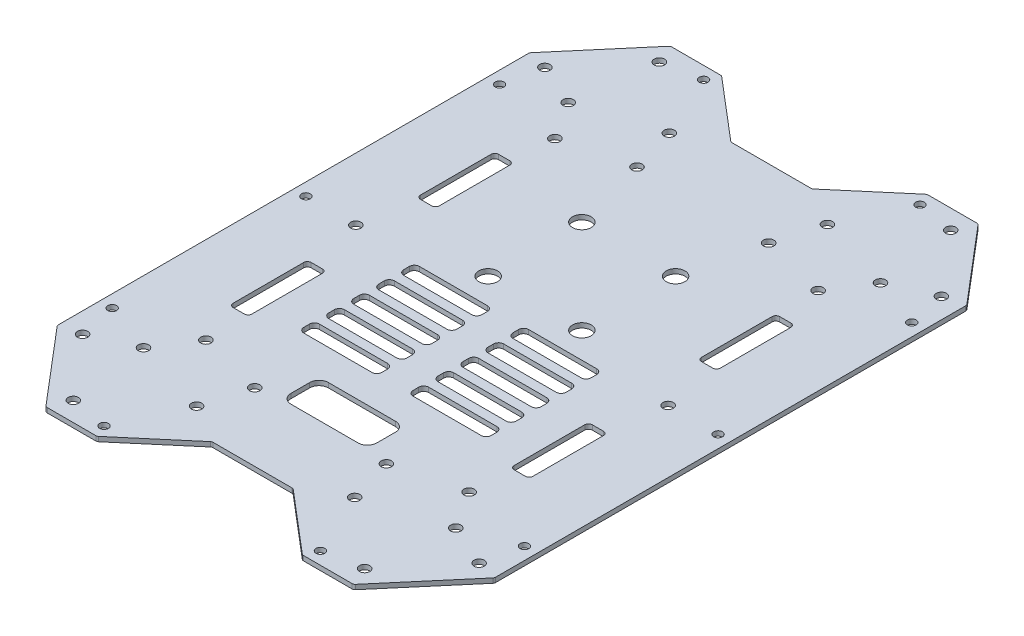
SolidWorks part; units mm, degrees
material "Custom Plastic"
ref_plane "Front Plane" through (0, 0, 0) normal (0, 0, 1) x (1, 0, 0)
ref_plane "Top Plane" through (0, 0, 0) normal (0, 1, 0) x (1, 0, 0)
ref_plane "Right Plane" through (0, 0, 0) normal (1, 0, 0) x (0, 0, -1)
sketch "Sketch1" plane through (0, 0, 0) normal (0, 1, 0) x (1, 0, 0)
  line L0 (49.2748, 100) -> (-49.2748, 100) construction
  line L1 (-49.2748, 100) -> (-70, 75.6183) construction
  line L2 (-70, -75.6183) -> (-70, 75.6183) construction
  line L3 (-49.2748, -100) -> (-70, -75.6183) construction
  line L4 (49.2748, -100) -> (-49.2748, -100) construction
  line L5 (49.2748, -100) -> (70, -75.6183) construction
  line L6 (70, -75.6183) -> (70, 75.6183) construction
  line L7 (49.2748, 100) -> (70, 75.6183) construction
  line L8 (49.2748, 100) -> (-49.2748, 100)
  line L9 (-49.2748, 100) -> (-70, 75.6183)
  line L10 (-70, -75.6183) -> (-70, 75.6183)
  line L11 (-49.2748, -100) -> (-70, -75.6183)
  line L12 (49.2748, -100) -> (-49.2748, -100)
  line L13 (49.2748, -100) -> (70, -75.6183)
  line L14 (70, -75.6183) -> (70, 75.6183)
  line L15 (49.2748, 100) -> (70, 75.6183)
  line L16 (247.4874, -247.4874) -> (29.1603, -61.9027) construction
  line L18 (-29.1603, -61.9027) -> (-247.4874, -247.4874) construction
  line L20 (-247.4874, 247.4874) -> (-29.1603, 61.9027) construction
  line L21 (247.4874, 247.4874) -> (29.1603, 61.9027) construction
  line L22 (247.4874, -247.4874) -> (29.1603, -61.9027) construction
  line L24 (-29.1603, -61.9027) -> (-247.4874, -247.4874) construction
  line L26 (-247.4874, 247.4874) -> (-29.1603, 61.9027) construction
  line L27 (247.4874, 247.4874) -> (29.1603, 61.9027) construction
extrude "Boss-Extrude1" add sketch "Sketch1" along normal blind 1.5
sketch "Sketch2" plane through (0, 0, 0) normal (0, 1, 0) x (1, 0, 0)
  line L0 (0, 100) -> (0, -100) construction
  line L1 (49.2748, 100) -> (-49.2748, 100) construction
  line L2 (49.2748, -100) -> (-49.2748, -100) construction
  line L8 (42, 18.7) -> (42, 41.3)
  line L47 (43.2, 17.5) -> (46.8, 17.5)
  line L48 (48, 18.7) -> (48, 41.3)
  line L49 (43.2, 42.5) -> (46.8, 42.5)
  line L50 (-48, 18.7) -> (-48, 41.3)
  line L51 (-46.8, 17.5) -> (-43.2, 17.5)
  line L52 (-42, 18.7) -> (-42, 41.3)
  line L53 (-46.8, 42.5) -> (-43.2, 42.5)
  line L54 (-70, 0) -> (70, 0) construction
  line L55 (-70, 75.6183) -> (-70, -75.6183) construction
  line L56 (70, -75.6183) -> (70, 75.6183) construction
  line L59 (-46.8, -42.5) -> (-43.2, -42.5)
  line L60 (-42, -18.7) -> (-42, -41.3)
  line L61 (-46.8, -17.5) -> (-43.2, -17.5)
  line L62 (-48, -18.7) -> (-48, -41.3)
  line L63 (43.2, -42.5) -> (46.8, -42.5)
  line L64 (48, -18.7) -> (48, -41.3)
  line L65 (43.2, -17.5) -> (46.8, -17.5)
  line L70 (42, -18.7) -> (42, -41.3)
  arc A40 (42, 41.3) -> (43.2, 42.5) centre (43.2, 41.3) cw
  arc A41 (43.2, 17.5) -> (42, 18.7) centre (43.2, 18.7) cw
  arc A42 (48, 18.7) -> (46.8, 17.5) centre (46.8, 18.7) cw
  arc A43 (46.8, 42.5) -> (48, 41.3) centre (46.8, 41.3) cw
  arc A44 (-48, 41.3) -> (-46.8, 42.5) centre (-46.8, 41.3) cw
  arc A45 (-46.8, 17.5) -> (-48, 18.7) centre (-46.8, 18.7) cw
  arc A46 (-42, 18.7) -> (-43.2, 17.5) centre (-43.2, 18.7) cw
  arc A47 (-43.2, 42.5) -> (-42, 41.3) centre (-43.2, 41.3) cw
  arc A48 (-43.2, -42.5) -> (-42, -41.3) centre (-43.2, -41.3) ccw
  arc A49 (-42, -18.7) -> (-43.2, -17.5) centre (-43.2, -18.7) ccw
  arc A50 (-46.8, -17.5) -> (-48, -18.7) centre (-46.8, -18.7) ccw
  arc A51 (-48, -41.3) -> (-46.8, -42.5) centre (-46.8, -41.3) ccw
  arc A52 (46.8, -42.5) -> (48, -41.3) centre (46.8, -41.3) ccw
  arc A53 (48, -18.7) -> (46.8, -17.5) centre (46.8, -18.7) ccw
  arc A54 (43.2, -17.5) -> (42, -18.7) centre (43.2, -18.7) ccw
  arc A55 (42, -41.3) -> (43.2, -42.5) centre (43.2, -41.3) ccw
extrude "Cut-Extrude1" cut sketch "Sketch2" along normal through all
sketch "Sketch3" plane through (0, 0, 0) normal (0, 1, 0) x (1, 0, 0)
  circle A0 centre (-25.3123, -75.6937) radius 1.65
  circle A1 centre (-46.6462, -93.8282) radius 1.65
  circle A2 centre (-63.4854, -74.0181) radius 1.65
  circle A3 centre (-42.1515, -55.8836) radius 1.65
  circle A4 centre (25.3123, -75.6937) radius 1.65
  circle A5 centre (46.6462, -93.8282) radius 1.65
  circle A6 centre (63.4854, -74.0181) radius 1.65
  circle A7 centre (42.1515, -55.8836) radius 1.65
  circle A8 centre (42.1515, 55.8836) radius 1.65
  circle A9 centre (63.4854, 74.0181) radius 1.65
  circle A10 centre (46.6462, 93.8282) radius 1.65
  circle A11 centre (25.3123, 75.6937) radius 1.65
  circle A12 centre (-25.3123, 75.6937) radius 1.65
  circle A13 centre (-42.1515, 55.8836) radius 1.65
  circle A14 centre (-63.4854, 74.0181) radius 1.65
  circle A15 centre (-46.6462, 93.8282) radius 1.65
  dimension "D1" = 3.3
extrude "Cut-Extrude2" cut sketch "Sketch3" along normal through all
sketch "Sketch5" plane through (0, 0, 0) normal (0, 1, 0) x (1, 0, 0)
  line L0 (50, -90) -> (50, 90) construction
  line L1 (-20, -20) -> (20, -20) construction
  line L2 (-20, -20) -> (-20, 20) construction
  line L3 (-20, 20) -> (20, 20) construction
  line L4 (20, -20) -> (20, 20) construction
  line L5 (-20, -20) -> (20, 20) construction
  line L6 (-20, 20) -> (20, -20) construction
  line L7 (48.7071, -90) -> (51.2929, -90) construction
  line L8 (48.7071, 90) -> (51.2929, 90) construction
  circle A14 centre (21.059, -61.2942) radius 1.65
  circle A15 centre (-21.105, -61.2942) radius 1.65
  circle A16 centre (21.059, 61.1338) radius 1.65
  circle A17 centre (-21.105, 61.1338) radius 1.65
  circle A18 centre (15.358, 37.0178) radius 3
  circle A19 centre (-14.642, 37.0178) radius 3
  circle A20 centre (-14.642, 7.0178) radius 3
  circle A21 centre (15.358, 7.0178) radius 3
  point P0 (0, 0)
  dimension "D1" = 3.3
  dimension "D4" = 6
  dimension "D2" = 40
  dimension "D3" = 40
extrude "Cut-Extrude5" cut sketch "Sketch5" along normal through all
sketch "Sketch6" plane through (0, 0, 0) normal (0, 1, 0) x (1, 0, 0)
  line L0 (-50, -90) -> (-50, 90) construction
  line L1 (-51.2929, -90) -> (-48.7071, -90) construction
  line L2 (-51.2929, 90) -> (-48.7071, 90) construction
  line L3 (0, -100) -> (0, 100) construction
  line L4 (-49.2748, -100) -> (49.2748, -100) construction
  line L5 (49.2748, 100) -> (-49.2748, 100) construction
  line L6 (50, -90) -> (50, 90) construction
  circle A0 centre (-50, 0) radius 1.65
  circle A1 centre (-50, -68) radius 1.65
  circle A2 centre (-50, 68) radius 1.65
  circle A3 centre (50, 68) radius 1.65
  circle A4 centre (50, -68) radius 1.65
  circle A5 centre (50, 0) radius 1.65
  dimension "D1" = 3.3
  dimension "D2" = 68
  dimension "D3" = 68
extrude "Cut-Extrude6" cut sketch "Sketch6" along normal through all
sketch "Sketch7" plane through (0, 0, 0) normal (0, 1, 0) x (1, 0, 0)
  line L0 (0, -100) -> (0, 100) construction
  line L1 (-49.2748, -100) -> (49.2748, -100) construction
  line L2 (49.2748, 100) -> (-49.2748, 100) construction
  line L3 (-70, 75.6183) -> (-70, -75.6183) construction
  line L4 (-70, 0) -> (-66, 0) construction
  line L5 (70, 0) -> (66, 0) construction
  circle A0 centre (-34.6462, -96) radius 1.4
  circle A1 centre (-46.6462, -93.8282) radius 1.65 construction
  circle A2 centre (-66, -62.0181) radius 1.4
  circle A3 centre (-63.4854, -74.0181) radius 1.65 construction
  circle A4 centre (-66, 0) radius 1.4
  circle A5 centre (-66, 62.0181) radius 1.4
  circle A6 centre (-63.4854, 74.0181) radius 1.65 construction
  circle A7 centre (-34.6462, 96) radius 1.4
  circle A8 centre (-46.6462, 93.8282) radius 1.65 construction
  circle A9 centre (0, 96) radius 1.4
  circle A10 centre (0, -96) radius 1.4
  circle A11 centre (34.6462, 96) radius 1.4
  circle A12 centre (66, 62.0181) radius 1.4
  circle A13 centre (66, 0) radius 1.4
  circle A14 centre (66, -62.0181) radius 1.4
  circle A15 centre (34.6462, -96) radius 1.4
  dimension "D2" = 2.8
  dimension "D1" = 4
  dimension "D3" = 12
  dimension "D4" = 4
  dimension "D5" = 12
  dimension "D6" = 4
  dimension "D7" = 4
  dimension "D8" = 12
  dimension "D9" = 4
  dimension "D10" = 12
  dimension "D11" = 4
  dimension "D12" = 4
extrude "Cut-Extrude7" cut sketch "Sketch7" along normal through all
sketch "Sketch9" [suppressed] plane through (0, 0, 0) normal (0, 1, 0) x (1, 0, 0)
  line L0 (0, -100) -> (0, 100) construction
  line L1 (-49.2748, -100) -> (49.2748, -100) construction
  line L2 (49.2748, 100) -> (-49.2748, 100) construction
  line L4 (-14.5, 42.1059) -> (14.5, 42.1059)
  line L5 (-20, 36.6059) -> (-20, 7.6059)
  line L6 (-14.5, 2.1059) -> (14.5, 2.1059)
  line L7 (20, 36.6059) -> (20, 7.6059)
  line L8 (-20, 42.1059) -> (20, 2.1059) construction
  line L9 (-20, 2.1059) -> (20, 42.1059) construction
  arc A0 (-14.5, 42.1059) -> (-20, 36.6059) centre (-14.5, 36.6059) ccw
  arc A1 (14.5, 42.1059) -> (20, 36.6059) centre (14.5, 36.6059) cw
  arc A2 (14.5, 2.1059) -> (20, 7.6059) centre (14.5, 7.6059) ccw
  arc A3 (-20, 7.6059) -> (-14.5, 2.1059) centre (-14.5, 7.6059) ccw
  point P6 (0, 22.1059)
  dimension "D2" = 5.5
  dimension "D1" = 40
extrude "Cut-Extrude9" [suppressed] cut sketch "Sketch9" along normal through all
sketch "Sketch10" plane through (0, 0, 0) normal (0, 1, 0) x (1, 0, 0)
  line L0 (0, 100) -> (0, -100) construction
  line L1 (49.2748, 100) -> (-49.2748, 100) construction
  line L2 (-49.2748, -100) -> (49.2748, -100) construction
  line L3 (-5, -10.8698) -> (-5, -12.6698)
  line L4 (-10.75, -60.0405) -> (10.75, -60.0405)
  line L5 (-13.75, -57.0405) -> (-13.75, -51.0405)
  line L6 (-10.75, -48.0405) -> (10.75, -48.0405)
  line L7 (13.75, -57.0405) -> (13.75, -51.0405)
  line L8 (-13.75, -60.0405) -> (13.75, -48.0405) construction
  line L9 (-13.75, -48.0405) -> (13.75, -60.0405) construction
  line L10 (-6.6, -1.2698) -> (-28.4, -1.2698)
  line L11 (-5, -2.8698) -> (-5, -4.6698)
  line L12 (-6.6, -6.2698) -> (-28.4, -6.2698)
  line L13 (-30, -2.8698) -> (-30, -4.6698)
  line L14 (-5, -1.2698) -> (-30, -6.2698) construction
  line L15 (-5, -6.2698) -> (-30, -1.2698) construction
  line L16 (-6.6, -9.2698) -> (-28.4, -9.2698)
  line L17 (-30, -10.8698) -> (-30, -12.6698)
  line L18 (-6.6, -14.2698) -> (-28.4, -14.2698)
  line L19 (-5, -18.8698) -> (-5, -20.6698)
  line L20 (-6.6, -17.2698) -> (-28.4, -17.2698)
  line L21 (-30, -18.8698) -> (-30, -20.6698)
  line L22 (-6.6, -22.2698) -> (-28.4, -22.2698)
  line L23 (-5, -26.8698) -> (-5, -28.6698)
  line L24 (-6.6, -25.2698) -> (-28.4, -25.2698)
  line L25 (-30, -26.8698) -> (-30, -28.6698)
  line L26 (-6.6, -30.2698) -> (-28.4, -30.2698)
  line L27 (-5, -34.8698) -> (-5, -36.6698)
  line L28 (-6.6, -33.2698) -> (-28.4, -33.2698)
  line L29 (-30, -34.8698) -> (-30, -36.6698)
  line L30 (-6.6, -38.2698) -> (-28.4, -38.2698)
  line L31 (5, -6.2698) -> (30, -1.2698) construction
  line L32 (5, -1.2698) -> (30, -6.2698) construction
  line L33 (6.6, -38.2698) -> (28.4, -38.2698)
  line L34 (30, -34.8698) -> (30, -36.6698)
  line L35 (6.6, -33.2698) -> (28.4, -33.2698)
  line L36 (5, -34.8698) -> (5, -36.6698)
  line L37 (6.6, -30.2698) -> (28.4, -30.2698)
  line L38 (30, -26.8698) -> (30, -28.6698)
  line L39 (6.6, -25.2698) -> (28.4, -25.2698)
  line L40 (5, -26.8698) -> (5, -28.6698)
  line L41 (6.6, -22.2698) -> (28.4, -22.2698)
  line L42 (30, -18.8698) -> (30, -20.6698)
  line L43 (6.6, -17.2698) -> (28.4, -17.2698)
  line L44 (5, -18.8698) -> (5, -20.6698)
  line L45 (6.6, -14.2698) -> (28.4, -14.2698)
  line L46 (30, -10.8698) -> (30, -12.6698)
  line L47 (6.6, -9.2698) -> (28.4, -9.2698)
  line L48 (30, -2.8698) -> (30, -4.6698)
  line L49 (6.6, -6.2698) -> (28.4, -6.2698)
  line L50 (5, -2.8698) -> (5, -4.6698)
  line L51 (6.6, -1.2698) -> (28.4, -1.2698)
  line L52 (5, -10.8698) -> (5, -12.6698)
  arc A0 (-13.75, -51.0405) -> (-10.75, -48.0405) centre (-10.75, -51.0405) cw
  arc A1 (-10.75, -60.0405) -> (-13.75, -57.0405) centre (-10.75, -57.0405) cw
  arc A2 (10.75, -60.0405) -> (13.75, -57.0405) centre (10.75, -57.0405) ccw
  arc A3 (10.75, -48.0405) -> (13.75, -51.0405) centre (10.75, -51.0405) cw
  arc A4 (-28.4, -6.2698) -> (-30, -4.6698) centre (-28.4, -4.6698) cw
  arc A5 (-5, -4.6698) -> (-6.6, -6.2698) centre (-6.6, -4.6698) cw
  arc A6 (-6.6, -1.2698) -> (-5, -2.8698) centre (-6.6, -2.8698) cw
  arc A7 (-28.4, -1.2698) -> (-30, -2.8698) centre (-28.4, -2.8698) ccw
  arc A8 (-6.6, -9.2698) -> (-5, -10.8698) centre (-6.6, -10.8698) cw
  arc A9 (-5, -12.6698) -> (-6.6, -14.2698) centre (-6.6, -12.6698) cw
  arc A10 (-28.4, -9.2698) -> (-30, -10.8698) centre (-28.4, -10.8698) ccw
  arc A11 (-28.4, -14.2698) -> (-30, -12.6698) centre (-28.4, -12.6698) cw
  arc A12 (-6.6, -17.2698) -> (-5, -18.8698) centre (-6.6, -18.8698) cw
  arc A13 (-5, -20.6698) -> (-6.6, -22.2698) centre (-6.6, -20.6698) cw
  arc A14 (-28.4, -17.2698) -> (-30, -18.8698) centre (-28.4, -18.8698) ccw
  arc A15 (-28.4, -22.2698) -> (-30, -20.6698) centre (-28.4, -20.6698) cw
  arc A16 (-6.6, -25.2698) -> (-5, -26.8698) centre (-6.6, -26.8698) cw
  arc A17 (-5, -28.6698) -> (-6.6, -30.2698) centre (-6.6, -28.6698) cw
  arc A18 (-28.4, -25.2698) -> (-30, -26.8698) centre (-28.4, -26.8698) ccw
  arc A19 (-28.4, -30.2698) -> (-30, -28.6698) centre (-28.4, -28.6698) cw
  arc A20 (-6.6, -33.2698) -> (-5, -34.8698) centre (-6.6, -34.8698) cw
  arc A21 (-5, -36.6698) -> (-6.6, -38.2698) centre (-6.6, -36.6698) cw
  arc A22 (-28.4, -33.2698) -> (-30, -34.8698) centre (-28.4, -34.8698) ccw
  arc A23 (-28.4, -38.2698) -> (-30, -36.6698) centre (-28.4, -36.6698) cw
  arc A25 (28.4, -38.2698) -> (30, -36.6698) centre (28.4, -36.6698) ccw
  arc A26 (28.4, -33.2698) -> (30, -34.8698) centre (28.4, -34.8698) cw
  arc A27 (5, -36.6698) -> (6.6, -38.2698) centre (6.6, -36.6698) ccw
  arc A28 (6.6, -33.2698) -> (5, -34.8698) centre (6.6, -34.8698) ccw
  arc A29 (28.4, -30.2698) -> (30, -28.6698) centre (28.4, -28.6698) ccw
  arc A30 (28.4, -25.2698) -> (30, -26.8698) centre (28.4, -26.8698) cw
  arc A31 (5, -28.6698) -> (6.6, -30.2698) centre (6.6, -28.6698) ccw
  arc A32 (6.6, -25.2698) -> (5, -26.8698) centre (6.6, -26.8698) ccw
  arc A33 (28.4, -22.2698) -> (30, -20.6698) centre (28.4, -20.6698) ccw
  arc A34 (28.4, -17.2698) -> (30, -18.8698) centre (28.4, -18.8698) cw
  arc A35 (5, -20.6698) -> (6.6, -22.2698) centre (6.6, -20.6698) ccw
  arc A36 (6.6, -17.2698) -> (5, -18.8698) centre (6.6, -18.8698) ccw
  arc A37 (28.4, -14.2698) -> (30, -12.6698) centre (28.4, -12.6698) ccw
  arc A38 (28.4, -9.2698) -> (30, -10.8698) centre (28.4, -10.8698) cw
  arc A39 (5, -12.6698) -> (6.6, -14.2698) centre (6.6, -12.6698) ccw
  arc A40 (6.6, -9.2698) -> (5, -10.8698) centre (6.6, -10.8698) ccw
  arc A41 (28.4, -1.2698) -> (30, -2.8698) centre (28.4, -2.8698) cw
  arc A42 (6.6, -1.2698) -> (5, -2.8698) centre (6.6, -2.8698) ccw
  arc A43 (5, -4.6698) -> (6.6, -6.2698) centre (6.6, -4.6698) ccw
  arc A44 (28.4, -6.2698) -> (30, -4.6698) centre (28.4, -4.6698) ccw
  point P6 (0, -54.0405)
  point P23 (-17.5, -3.7698)
  point P153 (17.5, -3.7698)
  dimension "D1" = 3
  dimension "D7" = 1.6
  dimension "D2" = 12
  dimension "D3" = 27.5
  dimension "D4" = 5
  dimension "D5" = 25
  dimension "D6" = 5
  dimension "D8" = 5
extrude "Cut-Extrude10" cut sketch "Sketch10" along normal through all
sketch "Sketch11" plane through (0, 0, 0) normal (0, 1, 0) x (1, 0, 0)
  line L0 (-17.4104, 71.0935) -> (17.4104, 71.0935) construction
  line L1 (17.4104, 71.0935) -> (50.1733, 98.943) construction
  line L2 (70, 75.6183) -> (49.2748, 100) construction
  line L3 (50.1733, 98.943) -> (50.1733, 117.8901) construction
  line L4 (-17.4104, 71.0935) -> (-50.1733, 98.943) construction
  line L5 (-49.2748, 100) -> (-70, 75.6183) construction
  line L6 (-50.1733, 98.943) -> (-50.1733, 117.8901) construction
  line L7 (-50.1733, 117.8901) -> (50.1733, 117.8901) construction
  line L8 (-12.9994, 83.0935) -> (-38.1733, 104.4921)
  line L9 (-38.1733, 104.4921) -> (-38.1733, 105.8901)
  line L10 (-38.1733, 105.8901) -> (38.1733, 105.8901)
  line L11 (38.1733, 104.4921) -> (38.1733, 105.8901)
  line L12 (12.9994, 83.0935) -> (38.1733, 104.4921)
  line L13 (-12.9994, 83.0935) -> (12.9994, 83.0935)
  line L14 (-70, 0) -> (70, 0) construction
  line L15 (-70, 75.6183) -> (-70, -75.6183) construction
  line L16 (70, -75.6183) -> (70, 75.6183) construction
  line L17 (-50.1733, -117.8901) -> (50.1733, -117.8901) construction
  line L18 (-50.1733, -98.943) -> (-50.1733, -117.8901) construction
  line L19 (-17.4104, -71.0935) -> (-50.1733, -98.943) construction
  line L20 (50.1733, -98.943) -> (50.1733, -117.8901) construction
  line L21 (17.4104, -71.0935) -> (50.1733, -98.943) construction
  line L22 (-17.4104, -71.0935) -> (17.4104, -71.0935) construction
  line L23 (-12.9994, -83.0935) -> (12.9994, -83.0935)
  line L24 (12.9994, -83.0935) -> (38.1733, -104.4921)
  line L25 (38.1733, -104.4921) -> (38.1733, -105.8901)
  line L26 (-38.1733, -105.8901) -> (38.1733, -105.8901)
  line L27 (-38.1733, -104.4921) -> (-38.1733, -105.8901)
  line L28 (-12.9994, -83.0935) -> (-38.1733, -104.4921)
  line L29 (49.2748, 100) -> (-49.2748, 100) construction
  dimension "D2" = 28.9065
  dimension "D3" = 5.8901
  dimension "D1" = 12
extrude "Cut-Extrude11" cut sketch "Sketch11" along normal through all
sketch "Sketch12" [suppressed] plane through (0, 0, 0) normal (0, 1, 0) x (1, 0, 0)
  line L0 (0, 83.0935) -> (0, -83.0935) construction
  line L1 (-12.9994, 83.0935) -> (12.9994, 83.0935) construction
  line L2 (12.9994, -83.0935) -> (-12.9994, -83.0935) construction
  line L3 (-30, -22.9) -> (-30, -21.1)
  line L4 (-28.4, -16.5) -> (-6.6, -16.5) construction
  line L5 (-30, -14.9) -> (-30, -13.1) construction
  line L6 (-28.4, -11.5) -> (-6.6, -11.5) construction
  line L7 (-5, -14.9) -> (-5, -13.1) construction
  line L8 (-30, -16.5) -> (-5, -11.5) construction
  line L9 (-30, -11.5) -> (-5, -16.5) construction
  line L10 (-28.4, -24.5) -> (-6.6, -24.5)
  line L11 (-5, -22.9) -> (-5, -21.1)
  line L12 (-28.4, -19.5) -> (-6.6, -19.5)
  line L13 (-30, -30.9) -> (-30, -29.1)
  line L14 (-28.4, -32.5) -> (-6.6, -32.5)
  line L15 (-5, -30.9) -> (-5, -29.1)
  line L16 (-28.4, -27.5) -> (-6.6, -27.5)
  line L17 (-30, -38.9) -> (-30, -37.1)
  line L18 (-28.4, -40.5) -> (-6.6, -40.5)
  line L19 (-5, -38.9) -> (-5, -37.1)
  line L20 (-28.4, -35.5) -> (-6.6, -35.5)
  line L21 (-30, -46.9) -> (-30, -45.1)
  line L22 (-28.4, -48.5) -> (-6.6, -48.5)
  line L23 (-5, -46.9) -> (-5, -45.1)
  line L24 (-28.4, -43.5) -> (-6.6, -43.5)
  line L25 (30, -11.5) -> (5, -16.5) construction
  line L26 (30, -16.5) -> (5, -11.5) construction
  line L27 (28.4, -43.5) -> (6.6, -43.5)
  line L28 (5, -46.9) -> (5, -45.1)
  line L29 (28.4, -48.5) -> (6.6, -48.5)
  line L30 (30, -46.9) -> (30, -45.1)
  line L31 (28.4, -35.5) -> (6.6, -35.5)
  line L32 (5, -38.9) -> (5, -37.1)
  line L33 (28.4, -40.5) -> (6.6, -40.5)
  line L34 (30, -38.9) -> (30, -37.1)
  line L35 (28.4, -27.5) -> (6.6, -27.5)
  line L36 (5, -30.9) -> (5, -29.1)
  line L37 (28.4, -32.5) -> (6.6, -32.5)
  line L38 (30, -30.9) -> (30, -29.1)
  line L39 (28.4, -19.5) -> (6.6, -19.5)
  line L40 (5, -22.9) -> (5, -21.1)
  line L41 (28.4, -24.5) -> (6.6, -24.5)
  line L42 (5, -14.9) -> (5, -13.1) construction
  line L43 (28.4, -11.5) -> (6.6, -11.5) construction
  line L44 (30, -14.9) -> (30, -13.1) construction
  line L45 (28.4, -16.5) -> (6.6, -16.5) construction
  line L46 (30, -22.9) -> (30, -21.1)
  line L47 (-42, -30) -> (42, -30) construction
  line L48 (-42, -41.3) -> (-42, -18.7) construction
  line L49 (42, -18.7) -> (42, -41.3) construction
  arc A0 (-30, -13.1) -> (-28.4, -11.5) centre (-28.4, -13.1) cw construction
  arc A1 (-28.4, -16.5) -> (-30, -14.9) centre (-28.4, -14.9) cw construction
  arc A2 (-6.6, -16.5) -> (-5, -14.9) centre (-6.6, -14.9) ccw construction
  arc A3 (-6.6, -11.5) -> (-5, -13.1) centre (-6.6, -13.1) cw construction
  arc A4 (-28.4, -24.5) -> (-30, -22.9) centre (-28.4, -22.9) cw
  arc A5 (-30, -21.1) -> (-28.4, -19.5) centre (-28.4, -21.1) cw
  arc A6 (-6.6, -24.5) -> (-5, -22.9) centre (-6.6, -22.9) ccw
  arc A7 (-6.6, -19.5) -> (-5, -21.1) centre (-6.6, -21.1) cw
  arc A8 (-28.4, -32.5) -> (-30, -30.9) centre (-28.4, -30.9) cw
  arc A9 (-30, -29.1) -> (-28.4, -27.5) centre (-28.4, -29.1) cw
  arc A10 (-6.6, -32.5) -> (-5, -30.9) centre (-6.6, -30.9) ccw
  arc A11 (-6.6, -27.5) -> (-5, -29.1) centre (-6.6, -29.1) cw
  arc A12 (-28.4, -40.5) -> (-30, -38.9) centre (-28.4, -38.9) cw
  arc A13 (-30, -37.1) -> (-28.4, -35.5) centre (-28.4, -37.1) cw
  arc A14 (-6.6, -40.5) -> (-5, -38.9) centre (-6.6, -38.9) ccw
  arc A15 (-6.6, -35.5) -> (-5, -37.1) centre (-6.6, -37.1) cw
  arc A16 (-28.4, -48.5) -> (-30, -46.9) centre (-28.4, -46.9) cw
  arc A17 (-30, -45.1) -> (-28.4, -43.5) centre (-28.4, -45.1) cw
  arc A18 (-6.6, -48.5) -> (-5, -46.9) centre (-6.6, -46.9) ccw
  arc A19 (-6.6, -43.5) -> (-5, -45.1) centre (-6.6, -45.1) cw
  arc A20 (6.6, -43.5) -> (5, -45.1) centre (6.6, -45.1) ccw
  arc A21 (6.6, -48.5) -> (5, -46.9) centre (6.6, -46.9) cw
  arc A22 (30, -45.1) -> (28.4, -43.5) centre (28.4, -45.1) ccw
  arc A23 (28.4, -48.5) -> (30, -46.9) centre (28.4, -46.9) ccw
  arc A24 (6.6, -35.5) -> (5, -37.1) centre (6.6, -37.1) ccw
  arc A25 (6.6, -40.5) -> (5, -38.9) centre (6.6, -38.9) cw
  arc A26 (30, -37.1) -> (28.4, -35.5) centre (28.4, -37.1) ccw
  arc A27 (28.4, -40.5) -> (30, -38.9) centre (28.4, -38.9) ccw
  arc A28 (6.6, -27.5) -> (5, -29.1) centre (6.6, -29.1) ccw
  arc A29 (6.6, -32.5) -> (5, -30.9) centre (6.6, -30.9) cw
  arc A30 (30, -29.1) -> (28.4, -27.5) centre (28.4, -29.1) ccw
  arc A31 (28.4, -32.5) -> (30, -30.9) centre (28.4, -30.9) ccw
  arc A32 (6.6, -19.5) -> (5, -21.1) centre (6.6, -21.1) ccw
  arc A33 (6.6, -24.5) -> (5, -22.9) centre (6.6, -22.9) cw
  arc A34 (30, -21.1) -> (28.4, -19.5) centre (28.4, -21.1) ccw
  arc A35 (28.4, -24.5) -> (30, -22.9) centre (28.4, -22.9) ccw
  arc A36 (6.6, -11.5) -> (5, -13.1) centre (6.6, -13.1) ccw construction
  arc A37 (6.6, -16.5) -> (5, -14.9) centre (6.6, -14.9) cw construction
  arc A38 (28.4, -16.5) -> (30, -14.9) centre (28.4, -14.9) ccw construction
  arc A39 (30, -13.1) -> (28.4, -11.5) centre (28.4, -13.1) ccw construction
  point P6 (-17.5, -14)
  point P135 (17.5, -14)
  point P136 (-5, -30)
  dimension "D4" = 1.6
  dimension "D1" = 25
  dimension "D2" = 5
  dimension "D3" = 5
  dimension "D5" = 5
extrude "Cut-Extrude12" [suppressed] cut sketch "Sketch12" along normal through all
fillet "Fillet1" radius 1 16 edges at (-70, 0.75, 75.6183) (-70, 0.75, -75.6183) (-49.2748, 0.75, -100) (-32.8886, 0.75, -100) (-12.9994, 0.75, -83.0935) (12.9994, 0.75, -83.0935) (32.8886, 0.75, -100) (49.2748, 0.75, -100) (70, 0.75, -75.6183) (70, 0.75, 75.6183) (49.2748, 0.75, 100) (32.8886, 0.75, 100) (12.9994, 0.75, 83.0935) (-12.9994, 0.75, 83.0935) (-32.8886, 0.75, 100) (-49.2748, 0.75, 100)
sketch "Sketch14" [suppressed] plane through (0, 1.5, 0) normal (0, 1, 0) x (1, 0, 0)
  circle A0 centre (-5.821, -62.1522) radius 2.5
  circle A1 centre (-13.021, -62.1522) radius 2.5
  circle A2 centre (5.775, -62.1522) radius 2.5
  circle A3 centre (12.975, -62.1522) radius 2.5
  dimension "D1" = 5
extrude "Cut-Extrude14" [suppressed] cut sketch "Sketch14" against normal through all both and the other way through all
sketch "Sketch15" [suppressed] plane through (0, 1.5, 0) normal (0, 1, 0) x (1, 0, 0)
  circle A0 centre (24.25, 54.6059) radius 1.6
  circle A1 centre (-24.25, 54.6059) radius 1.6
  circle A2 centre (-24.25, -10.3941) radius 1.6
  circle A3 centre (24.25, -10.3941) radius 1.6
  dimension "D1" = 3.2
sketch "Sketch16" [suppressed] plane through (0, 1.5, 0) normal (0, 1, 0) x (1, 0, 0)
  line L0 (-18.25, 51.6059) -> (-18.25, 47.6059)
  line L1 (-21.25, 44.6059) -> (-24.5, 44.6059)
  line L2 (-27.5, 41.6059) -> (-27.5, 2.6059)
  line L3 (-24.5, -0.3941) -> (-23.75, -0.3941)
  line L4 (-20.75, -3.3941) -> (-20.75, -10.3941)
  line L5 (-17.75, -13.3941) -> (17.75, -13.3941)
  line L6 (20.75, -10.3941) -> (20.75, -3.3941)
  line L7 (23.75, -0.3941) -> (24.5, -0.3941)
  line L8 (27.5, 2.6059) -> (27.5, 41.6059)
  line L9 (24.5, 44.6059) -> (21.25, 44.6059)
  line L10 (18.25, 47.6059) -> (18.25, 51.6059)
  line L11 (15.25, 54.6059) -> (-15.25, 54.6059)
  line L12 (-0.8, 58.6059) -> (-6.4011, 58.6059) construction
  line L13 (28.5, 40.7959) -> (28.5, 54.1059) construction
  line L14 (-28.5, 54.1059) -> (-28.5, 39.4059) construction
  line L15 (-24, -14.3941) -> (-12.05, -14.3941) construction
  circle A1 centre (-24.25, 54.6059) radius 2.85 construction
  circle A2 centre (24.25, 54.6059) radius 2.85 construction
  circle A3 centre (-24.25, -10.3941) radius 2.85 construction
  circle A4 centre (24.25, -10.3941) radius 2.85 construction
  arc A5 (-18.25, 47.6059) -> (-21.25, 44.6059) centre (-21.25, 47.6059) cw
  arc A6 (21.25, 44.6059) -> (18.25, 47.6059) centre (21.25, 47.6059) cw
  arc A7 (20.75, -3.3941) -> (23.75, -0.3941) centre (23.75, -3.3941) cw
  arc A8 (-23.75, -0.3941) -> (-20.75, -3.3941) centre (-23.75, -3.3941) cw
  arc A9 (17.75, -13.3941) -> (20.75, -10.3941) centre (17.75, -10.3941) ccw
  arc A10 (-20.75, -10.3941) -> (-17.75, -13.3941) centre (-17.75, -10.3941) ccw
  arc A11 (-18.25, 51.6059) -> (-15.25, 54.6059) centre (-15.25, 51.6059) cw
  arc A12 (18.25, 51.6059) -> (15.25, 54.6059) centre (15.25, 51.6059) ccw
  arc A13 (27.5, 41.6059) -> (24.5, 44.6059) centre (24.5, 41.6059) ccw
  arc A14 (24.5, -0.3941) -> (27.5, 2.6059) centre (24.5, 2.6059) ccw
  arc A15 (-27.5, 2.6059) -> (-24.5, -0.3941) centre (-24.5, 2.6059) ccw
  arc A16 (-24.5, 44.6059) -> (-27.5, 41.6059) centre (-24.5, 41.6059) ccw
  dimension "D9" = 10
  dimension "D11" = 3.5
  dimension "D13" = 3
  dimension "D14" = 3
  dimension "D1" = 4
  dimension "D2" = 1
  dimension "D3" = 1
  dimension "D4" = 1
  dimension "D5" = 6
  dimension "D6" = 6
  dimension "D7" = 10
  dimension "D8" = 10
  dimension "D10" = 10
  dimension "D12" = 3.5
extrude "Cut-Extrude15" [suppressed] cut sketch "Sketch16" against normal through all
extrude "Cut-Extrude16" [suppressed] cut sketch "Sketch15" against normal through all
